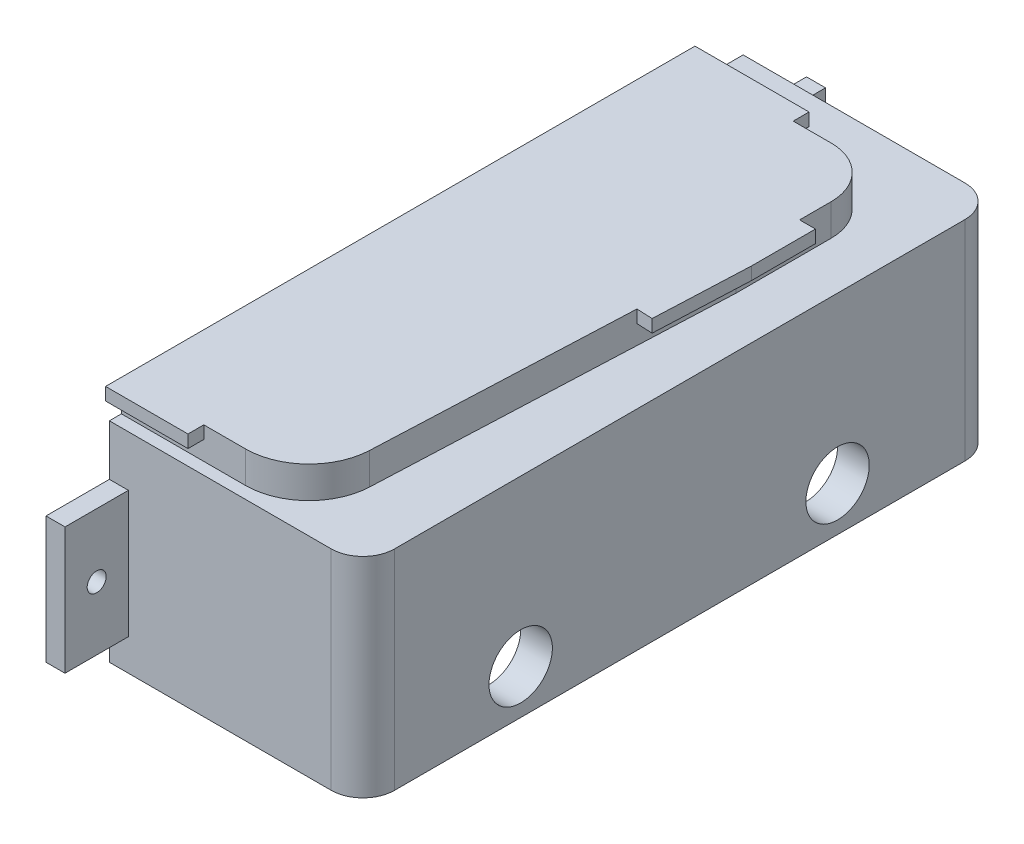
SolidWorks part; units mm, degrees
ref_plane "Front Plane" through (0, 0, 0) normal (0, 0, 1) x (1, 0, 0)
ref_plane "Top Plane" through (0, 0, 0) normal (0, 1, 0) x (1, 0, 0)
ref_plane "Right Plane" through (0, 0, 0) normal (1, 0, 0) x (0, 0, -1)
sketch "Sketch1" plane through (0, 0, 0) normal (0, 1, 0) x (1, 0, 0)
  line L0 (-32, 36) -> (-32, 21)
  line L3 (-24, 44) -> (24, 44)
  line L7 (32, 36) -> (32, 21)
  line L8 (-32, 21) -> (-29.5796, -34.4362)
  line L9 (-19.5891, -44) -> (19.5891, -44)
  line L10 (29.5796, -34.4362) -> (32, 21)
  line L11 (-24, 41) -> (24, 41)
  line L12 (29, 36) -> (29, 21.0655)
  line L13 (26.5825, -34.3053) -> (29, 21.0655)
  line L14 (-19.5891, -41) -> (19.5891, -41)
  line L15 (-29, 21.0655) -> (-26.5825, -34.3053)
  line L16 (-29, 36) -> (-29, 21.0655)
  line L17 (-35, -45.9) -> (35, -45.9)
  line L18 (-40, -40.9) -> (-40, 49.1)
  line L19 (-35, 54.1) -> (35, 54.1)
  line L20 (40, -40.9) -> (40, 49.1)
  arc A2 (-19.5891, -44) -> (-29.5796, -34.4362) centre (-19.5891, -34) cw
  arc A3 (29.5796, -34.4362) -> (19.5891, -44) centre (19.5891, -34) cw
  arc A4 (-24, 44) -> (-32, 36) centre (-24, 36) ccw
  arc A5 (32, 36) -> (24, 44) centre (24, 36) ccw
  arc A6 (29, 36) -> (24, 41) centre (24, 36) ccw
  arc A7 (26.5825, -34.3053) -> (19.5891, -41) centre (19.5891, -34) cw
  arc A8 (-19.5891, -41) -> (-26.5825, -34.3053) centre (-19.5891, -34) cw
  arc A9 (-24, 41) -> (-29, 36) centre (-24, 36) ccw
  arc A10 (-40, -40.9) -> (-35, -45.9) centre (-35, -40.9) ccw
  arc A11 (35, -45.9) -> (40, -40.9) centre (35, -40.9) ccw
  arc A12 (40, 49.1) -> (35, 54.1) centre (35, 49.1) ccw
  arc A13 (-35, 54.1) -> (-40, 49.1) centre (-35, 49.1) ccw
  point P0 (0, 0)
  point P32 (0, 4.1)
  dimension "D1" = 177.5
  dimension "D4" = 8
  dimension "D5" = 8
  dimension "D8" = 15
  dimension "D13" = 10
  dimension "D14" = 10
  dimension "D12" = 5
  dimension "D2" = 44
  dimension "D3" = 177.5
  dimension "D6" = 32
  dimension "D7" = 32
  dimension "D9" = 15
  dimension "D10" = 44
  dimension "D11" = 3
  dimension "D15" = 100
  dimension "D16" = 80
  dimension "D17" = 50
  dimension "D18" = 40
  dimension "D19" = 4.1
ref_plane "Plane1" through (0, 25, 0) normal (0, 1, 0) x (1, 0, 0)
sketch "Sketch8" plane through (0, 0, 0) normal (0, 1, 0) x (-1, 0, 0)
  line L0 (32, -36) -> (32, -21)
  line L1 (24, -44) -> (-24, -44)
  line L2 (-32, -36) -> (-32, -21)
  line L3 (32, -21) -> (29.5796, 34.4362)
  line L4 (19.5891, 44) -> (-19.5891, 44)
  line L5 (-29.5796, 34.4362) -> (-32, -21)
  line L7 (15.9, 11.8) -> (-15.9, -20) construction
  line L9 (-15.9, 11.8) -> (15.9, -20) construction
  arc A0 (19.5891, 44) -> (29.5796, 34.4362) centre (19.5891, 34) cw
  arc A1 (-29.5796, 34.4362) -> (-19.5891, 44) centre (-19.5891, 34) cw
  arc A2 (24, -44) -> (32, -36) centre (24, -36) ccw
  arc A3 (-32, -36) -> (-24, -44) centre (-24, -36) ccw
  circle A4 centre (15.9, 11.8) radius 10
  circle A8 centre (-15.9, 11.8) radius 10
  circle A9 centre (15.9, -20) radius 10
  circle A10 centre (-15.9, -20) radius 10
  point P0 (0, 0)
  point P28 (0, -4.1)
  dimension "D7" = 10
  dimension "D8" = 10
  dimension "D9" = 8
  dimension "D10" = 8
  dimension "D13" = 20
  dimension "D14" = 24
  dimension "D20" = 20
  dimension "D21" = 20
  dimension "D22" = 20
  dimension "D1" = 44
  dimension "D2" = 177.5
  dimension "D3" = 177.5
  dimension "D4" = 32
  dimension "D5" = 32
  dimension "D6" = 44
  dimension "D11" = 15
  dimension "D12" = 15
  dimension "D15" = 31.8
  dimension "D16" = 31.8
  dimension "D17" = 31.8
  dimension "D18" = 31.8
  dimension "D19" = 15.9
  dimension "D23" = 4.1
extrude "Boss-Extrude6" add sketch "Sketch8" against normal blind 5 separate body
extrude "Boss-Extrude7" add sketch "Sketch1" along normal blind 5 contours L19 A13 L18 A10 L17 A11 L20 A12 A5 L7 L10 A3 L9 A2 L8 L0 A4 L3 | L7 A5 L3 A4 L0 L8 A2 L9 A3 L10 A9 L11 A6 L12 L13 A7 L14 A8 L15 L16
ref_plane "Plane2" through (0, 38, 0) normal (0, 1, 0) x (1, 0, 0)
sketch "Sketch2" plane through (0, 25, 0) normal (0, 1, 0) x (1, 0, 0)
  line L1 (-35, -45.9) -> (35, -45.9)
  line L2 (-40, -40.9) -> (-40, 49.1)
  line L3 (-35, 54.1) -> (35, 54.1)
  line L4 (40, -40.9) -> (40, 49.1)
  arc A0 (-40, -40.9) -> (-35, -45.9) centre (-35, -40.9) ccw
  arc A1 (35, -45.9) -> (40, -40.9) centre (35, -40.9) ccw
  arc A2 (40, 49.1) -> (35, 54.1) centre (35, 49.1) ccw
  arc A3 (-35, 54.1) -> (-40, 49.1) centre (-35, 49.1) ccw
  point P0 (0, 4.1)
  dimension "D3" = 5
  dimension "D1" = 100
  dimension "D2" = 80
  dimension "D4" = 50
  dimension "D5" = 40
  dimension "D6" = 4.1
extrude "Extrude-Thin4" add sketch "Sketch2" against normal up to surface (20 mm away) and the other way blind 8 separate body thin contours L3 A2 L4 A1 L1 A0 L2 A3
sketch "Sketch10" plane through (0, 38, 0) normal (0, 1, 0) x (1, 0, 0)
  line L0 (-32, 36) -> (-32, 21)
  line L1 (-24, 44) -> (24, 44)
  line L2 (32, 36) -> (32, 21)
  line L3 (-32, 21) -> (-29.5796, -34.4362)
  line L4 (-19.5891, -44) -> (19.5891, -44)
  line L5 (29.5796, -34.4362) -> (32, 21)
  arc A0 (-19.5891, -44) -> (-29.5796, -34.4362) centre (-19.5891, -34) cw
  arc A1 (29.5796, -34.4362) -> (19.5891, -44) centre (19.5891, -34) cw
  arc A2 (-24, 44) -> (-32, 36) centre (-24, 36) ccw
  arc A3 (32, 36) -> (24, 44) centre (24, 36) ccw
  point P0 (0, 0)
  dimension "D7" = 10
  dimension "D8" = 10
  dimension "D9" = 8
  dimension "D10" = 8
  dimension "D1" = 44
  dimension "D2" = 177.5
  dimension "D3" = 177.5
  dimension "D4" = 32
  dimension "D5" = 32
  dimension "D6" = 44
  dimension "D11" = 15
  dimension "D12" = 15
extrude "Boss-Extrude8" add sketch "Sketch10" along normal blind 5 separate body
sketch "Sketch11" plane through (0, 38, 0) normal (0, 1, 0) x (1, 0, 0)
  line L0 (-35, -45.9) -> (35, -45.9)
  line L1 (-40, -40.9) -> (-40, 49.1)
  line L2 (-35, 54.1) -> (35, 54.1)
  line L3 (40, -40.9) -> (40, 49.1)
  line L4 (-35, 54.1) -> (35, 54.1) construction
  line L5 (40, -40.9) -> (40, 49.1) construction
  line L6 (-35, -45.9) -> (35, -45.9) construction
  arc A0 (-40, -40.9) -> (-35, -45.9) centre (-35, -40.9) ccw
  arc A1 (35, -45.9) -> (40, -40.9) centre (35, -40.9) ccw
  arc A2 (40, 49.1) -> (35, 54.1) centre (35, 49.1) ccw
  arc A3 (-35, 54.1) -> (-40, 49.1) centre (-35, 49.1) ccw
  dimension "D1" = 5
extrude "Boss-Extrude9" add sketch "Sketch11" against normal blind 5
sketch "Sketch13" plane through (0, 0, 0) normal (1, 0, 0) x (0, 0, -1)
  line L1 (49.1, 11.1) -> (42.6, 11.1)
  line L2 (49.1, 11.1) -> (49.1, 28.9)
  line L3 (49.1, 28.9) -> (42.6, 28.9)
  line L4 (42.6, 11.1) -> (42.6, 28.9)
  line L5 (-34.6, 11.1) -> (-40.9, 11.1)
  line L6 (-34.6, 11.1) -> (-34.6, 28.9)
  line L7 (-34.6, 28.9) -> (-40.9, 28.9)
  line L8 (-40.9, 11.1) -> (-40.9, 28.9)
  line L9 (-40.9, 33) -> (-40.9, 5) construction
  line L10 (49.1, 33) -> (49.1, 5) construction
  dimension "D1" = 17.8
  dimension "D2" = 6.5
  dimension "D3" = 11.1
  dimension "D4" = 17.8
  dimension "D5" = 6.3
  dimension "D6" = 11.1
extrude "Boss-Extrude10" add sketch "Sketch13" along normal through all and the other way through all
sketch "Sketch15" plane through (0, 11.1, 0) normal (0, -1, 0) x (1, 0, 0)
  line L0 (35, -49.1) -> (-35, -49.1) construction
  line L1 (-35, -42.6) -> (-35, -49.1) construction
  line L3 (-35, 40.9) -> (-35, 34.6) construction
  line L4 (-35, 40.9) -> (35, 40.9) construction
  line L6 (0, -26.4) -> (0, 26.4) construction
  circle A0 centre (-22, -44) radius 2
  circle A1 centre (-10, -44) radius 2
  circle A2 centre (-22, 36) radius 2
  circle A3 centre (-10, 36) radius 2
  circle A4 centre (10, 36) radius 2
  circle A5 centre (22, 36) radius 2
  circle A6 centre (10, -44) radius 2
  circle A7 centre (22, -44) radius 2
  dimension "D1" = 5.1
  dimension "D2" = 4
  dimension "D5" = 4
  dimension "D6" = 4
  dimension "D8" = 4
  dimension "D3" = 13
  dimension "D4" = 12
  dimension "D7" = 12
  dimension "D9" = 4.9
  dimension "D10" = 13
extrude "Cut-Extrude1" cut sketch "Sketch15" against normal up to surface (17.8 mm away) contours A5
sketch "Sketch17" plane through (0, -5, 0) normal (0, 1, 0) x (1, 0, 0)
  line L0 (0, 0) -> (0, 54.1) construction
  line L5 (18, 46.5) -> (18, 43.5)
  line L6 (18, 46.5) -> (-18, 46.5)
  line L7 (18, 43.5) -> (-18, 43.5)
  line L8 (-18, 46.5) -> (-18, 43.5)
  line L9 (18, 46.5) -> (-18, 43.5) construction
  line L10 (18, 43.5) -> (-18, 46.5) construction
  line L11 (-35, 54.1) -> (35, 54.1) construction
  line L12 (-13, -46.5) -> (13, -46.5)
  line L13 (-13, -46.5) -> (-13, -43.5)
  line L14 (-13, -43.5) -> (13, -43.5)
  line L15 (13, -46.5) -> (13, -43.5)
  line L16 (-13, -46.5) -> (13, -43.5) construction
  line L17 (-13, -43.5) -> (13, -46.5) construction
  line L19 (-31.5, 21.0109) -> (-30.8457, 6.0252)
  line L21 (-30.8457, 6.0252) -> (-33.8429, 5.8943)
  line L22 (-33.8429, 5.8943) -> (-34.5, 20.9454)
  line L24 (-34.5, 31.0109) -> (-34.5, 20.9454)
  line L25 (-31.5, 31.0109) -> (-34.5, 31.0109)
  line L27 (24, 44) -> (-24, 44) construction
  line L31 (29.0801, -34.4144) -> (31.5, 21.0109) construction
  line L32 (31.5, 21.0109) -> (31.5, 31.0109) construction
  line L33 (-31.5, 21.0109) -> (-31.5, 31.0109)
  line L40 (31.5, 21.0109) -> (31.5, 31.0109)
  line L41 (31.5, 31.0109) -> (34.5, 31.0109)
  line L46 (34.5, 31.0109) -> (34.5, 20.9454)
  line L47 (31.5, 21.0109) -> (30.8457, 6.0252)
  line L48 (30.8457, 6.0252) -> (33.8429, 5.8943)
  line L49 (33.8429, 5.8943) -> (34.5, 20.9454)
  point P1 (0, 45)
  point P3 (0, -45)
  dimension "D1" = 36
  dimension "D2" = 3
  dimension "D3" = 3
  dimension "D4" = 26
  dimension "D5" = 0.5
  dimension "D7" = 3
  dimension "D8" = 3
  dimension "D12" = 10
  dimension "D13" = 15
sketch "Sketch18" plane through (0, 43, 0) normal (0, 1, 0) x (1, 0, 0)
  line L5 (18, 46.5) -> (18, 43.5)
  line L6 (18, 46.5) -> (-18, 46.5)
  line L7 (18, 43.5) -> (-18, 43.5)
  line L8 (-18, 46.5) -> (-18, 43.5)
  line L9 (18, 46.5) -> (-18, 43.5) construction
  line L10 (18, 43.5) -> (-18, 46.5) construction
  line L12 (-13, -46.5) -> (13, -46.5)
  line L13 (-13, -46.5) -> (-13, -43.5)
  line L14 (-13, -43.5) -> (13, -43.5)
  line L15 (13, -46.5) -> (13, -43.5)
  line L16 (-13, -46.5) -> (13, -43.5) construction
  line L17 (-13, -43.5) -> (13, -46.5) construction
  line L19 (-31.5, 21.0109) -> (-30.8457, 6.0252)
  line L21 (-30.8457, 6.0252) -> (-33.8429, 5.8943)
  line L22 (-33.8429, 5.8943) -> (-34.5, 20.9454)
  line L24 (-34.5, 31.0109) -> (-34.5, 20.9454)
  line L25 (-31.5, 31.0109) -> (-34.5, 31.0109)
  line L31 (29.0801, -34.4144) -> (31.5, 21.0109) construction
  line L32 (31.5, 21.0109) -> (31.5, 31.0109) construction
  line L33 (-31.5, 21.0109) -> (-31.5, 31.0109)
  line L40 (31.5, 21.0109) -> (31.5, 31.0109)
  line L41 (31.5, 31.0109) -> (34.5, 31.0109)
  line L46 (34.5, 31.0109) -> (34.5, 20.9454)
  line L47 (31.5, 21.0109) -> (30.8457, 6.0252)
  line L48 (30.8457, 6.0252) -> (33.8429, 5.8943)
  line L49 (33.8429, 5.8943) -> (34.5, 20.9454)
  point P1 (0, 45)
  point P3 (0, -45)
  dimension "D1" = 36
  dimension "D2" = 3
  dimension "D3" = 3
  dimension "D4" = 26
  dimension "D7" = 3
  dimension "D8" = 3
  dimension "D12" = 10
  dimension "D13" = 15
extrude "Boss-Extrude11" add sketch "Sketch17" along normal blind 2
extrude "Boss-Extrude12" add sketch "Sketch18" against normal blind 2
ref_plane "Plane6" through (0, 5, 0) normal (0, 1, 0) x (1, 0, 0)
sketch "Sketch19" plane through (0, 0, 0) normal (1, 0, 0) x (0, 0, -1)
  line L0 (-45.9, 30) -> (-55.9, 30)
  line L1 (64.1, 30) -> (54.1, 30)
  line L2 (64.1, 30) -> (64.1, 10)
  line L3 (64.1, 10) -> (54.1, 10)
  line L4 (54.1, 30) -> (54.1, 10)
  line L5 (64.1, 30) -> (54.1, 10) construction
  line L6 (64.1, 10) -> (54.1, 30) construction
  line L7 (-45.9, 30) -> (-45.9, 10)
  line L8 (-45.9, 10) -> (-55.9, 10)
  line L9 (-55.9, 30) -> (-55.9, 10)
  line L10 (-45.9, 30) -> (-55.9, 10) construction
  line L11 (-45.9, 10) -> (-55.9, 30) construction
  circle A0 centre (59.1, 20) radius 1.5
  circle A1 centre (-50.9, 20) radius 1.5
  point P0 (59.1, 20)
  point P9 (-50.9, 20)
  dimension "D5" = 3
  dimension "D6" = 3
  dimension "D1" = 54.1
  dimension "D2" = 10
  dimension "D3" = 20
  dimension "D4" = 10
  dimension "D7" = 45.9
  dimension "D8" = 10
  dimension "D9" = 20
  dimension "D10" = 10
extrude "Boss-Extrude13" add sketch "Sketch19" along normal blind 3 and the other way blind 3
ref_plane "Plane7" through (0, 0, 38) normal (0, 0, 1) x (1, 0, 0)
sketch "Sketch21" plane through (0, 0, 38) normal (0, 0, 1) x (1, 0, 0)
  circle A0 centre (0, 20) radius 2.5
  dimension "D1" = 5
  dimension "D2" = 20
ref_plane "Plane8" through (0, 0, -46.2) normal (0, 0, 1) x (1, 0, 0)
sketch "Sketch23" plane through (0, 0, -46.2) normal (0, 0, 1) x (1, 0, 0)
  circle A0 centre (0, 20) radius 2.5
  dimension "D1" = 5
  dimension "D2" = 20
extrude "Cut-Extrude5" cut sketch "Sketch21" along normal blind 8
extrude "Cut-Extrude6" cut sketch "Sketch23" against normal blind 8
sketch "Sketch24" plane through (0, 5, 0) normal (0, 1, 0) x (1, 0, 0)
  line L1 (75, -75) -> (-75, -75)
  line L2 (75, -75) -> (75, 75)
  line L3 (75, 75) -> (-75, 75)
  line L4 (-75, -75) -> (-75, 75)
  line L5 (75, -75) -> (-75, 75) construction
  line L6 (75, 75) -> (-75, -75) construction
  point P0 (0, 0)
extrude "Cut-Extrude7" cut sketch "Sketch24" against normal through all
sketch "Sketch25" plane through (0, 0, 0) normal (1, 0, 0) x (0, 0, -1)
  line L1 (-75, -75) -> (75, -75)
  line L2 (-75, -75) -> (-75, 75)
  line L3 (-75, 75) -> (75, 75)
  line L4 (75, -75) -> (75, 75)
  line L5 (-75, -75) -> (75, 75) construction
  line L6 (-75, 75) -> (75, -75) construction
  point P0 (0, 0)
extrude "Cut-Extrude8" cut sketch "Sketch25" against normal through all
sketch "Sketch26" plane through (0, 11.1, 0) normal (0, -1, 0) x (1, 0, 0)
  line L0 (35, -42.6) -> (23.4283, -42.6) construction
  line L1 (35, -49.1) -> (27.84, -49.1)
  line L2 (35, -49.1) -> (35, -42.6)
  line L3 (35, -42.6) -> (27.84, -42.6)
  line L4 (27.84, -49.1) -> (27.84, -42.6)
  line L5 (35, 34.6) -> (23.4283, 34.6) construction
  line L6 (35, 40.9) -> (28.7, 40.9)
  line L7 (35, 40.9) -> (35, 34.6)
  line L8 (35, 34.6) -> (28.7, 34.6)
  line L9 (28.7, 40.9) -> (28.7, 34.6)
extrude "Boss-Extrude14" add sketch "Sketch26" along normal up to surface (6.1 mm away) up to face at (22.2071, 5, -4.1)
sketch "Sketch27" plane through (0, 5, 0) normal (0, -1, 0) x (1, 0, 0)
  circle A0 centre (35, 40.9) radius 2
  circle A1 centre (35, -49.1) radius 2
  arc A2 (35, -54.1) -> (40, -49.1) centre (35, -49.1) ccw construction
  arc A3 (40, 40.9) -> (35, 45.9) centre (35, 40.9) ccw construction
  dimension "D1" = 4
  dimension "D2" = 4
extrude "Cut-Extrude9" cut sketch "Sketch27" against normal blind 8
sketch "Sketch28" plane through (0, 33, 0) normal (0, -1, 0) x (1, 0, 0)
  line L0 (0, -49.1) -> (35, -49.1) construction
  line L1 (23.5, 2.6) -> (8.5, 2.6)
  line L2 (23.5, 2.6) -> (23.5, -10.8)
  line L3 (23.5, -10.8) -> (8.5, -10.8)
  line L4 (8.5, 2.6) -> (8.5, -10.8)
  line L5 (23.5, 2.6) -> (8.5, -10.8) construction
  line L6 (23.5, -10.8) -> (8.5, 2.6) construction
  line L7 (0, 40.9) -> (35, 40.9) construction
  line L8 (35, 40.9) -> (35, -49.1) construction
  point P0 (16, -4.1)
  dimension "D1" = 38.3
  dimension "D2" = 38.3
  dimension "D3" = 15
  dimension "D4" = 19
extrude "Boss-Extrude15" add sketch "Sketch28" along normal blind 15
sketch "Sketch29" plane through (0, 0, 0) normal (-1, 0, 0) x (0, 0, 1)
  circle A0 centre (-29, 12) radius 5
  circle A1 centre (21, 12) radius 5
  dimension "D1" = 12
  dimension "D3" = 10
  dimension "D4" = 10
  dimension "D2" = 12
  dimension "D5" = 29
  dimension "D6" = 21
extrude "Cut-Extrude10" cut sketch "Sketch29" against normal through all and the other way through all
